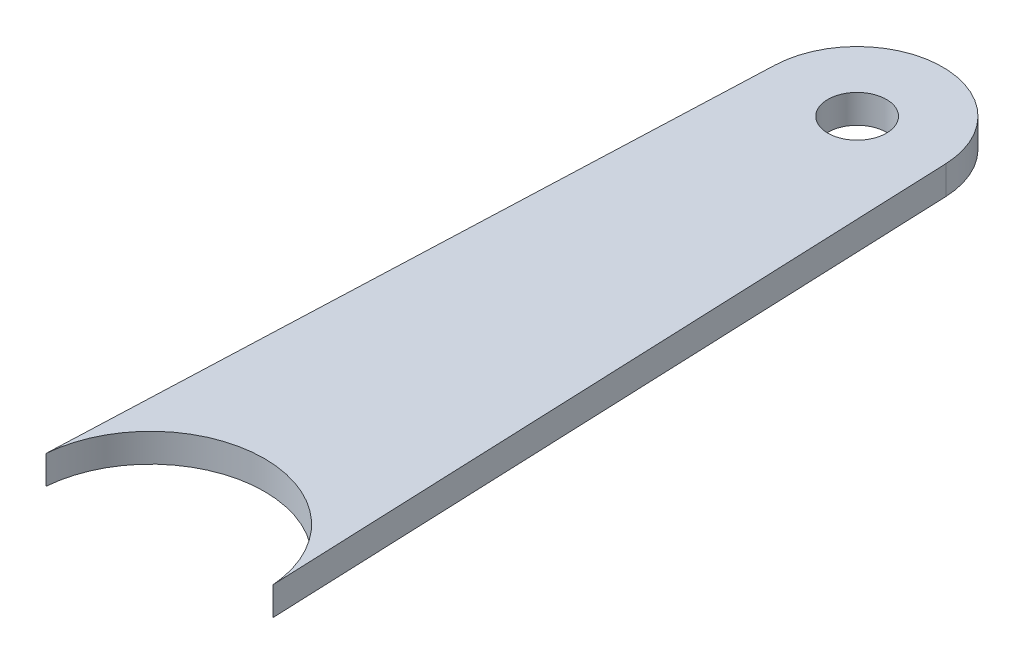
SolidWorks part; units mm, degrees
ref_plane "Front Plane" through (0, 0, 0) normal (0, 0, 1) x (1, 0, 0)
ref_plane "Top Plane" through (0, 0, 0) normal (0, 1, 0) x (1, 0, 0)
ref_plane "Right Plane" through (0, 0, 0) normal (1, 0, 0) x (0, 0, -1)
sketch "Sketch1" plane through (0, 0, 0) normal (0, 1, 0) x (1, 0, 0)
  line L0 (0, 0) -> (25.4, 0)
  line L1 (25.4, 0) -> (22.2173, 79.138)
  line L2 (0, 0) -> (3.1827, 79.138)
  arc A0 (22.2173, 79.138) -> (3.1827, 79.138) centre (12.7, 78.7552) ccw
  circle A1 centre (12.7, 78.7552) radius 3.2639
  circle A2 centre (12.7, 0) radius 12.7
  point P6 (12.7, 0)
  dimension "D2" = 6.5278
  dimension "D3" = 9.525
  dimension "D1" = 78.7552
  dimension "D4" = 25.4
extrude "Boss-Extrude2" add sketch "Sketch1" along normal blind 3.175 contours A2 L1 A0 L2 A1
